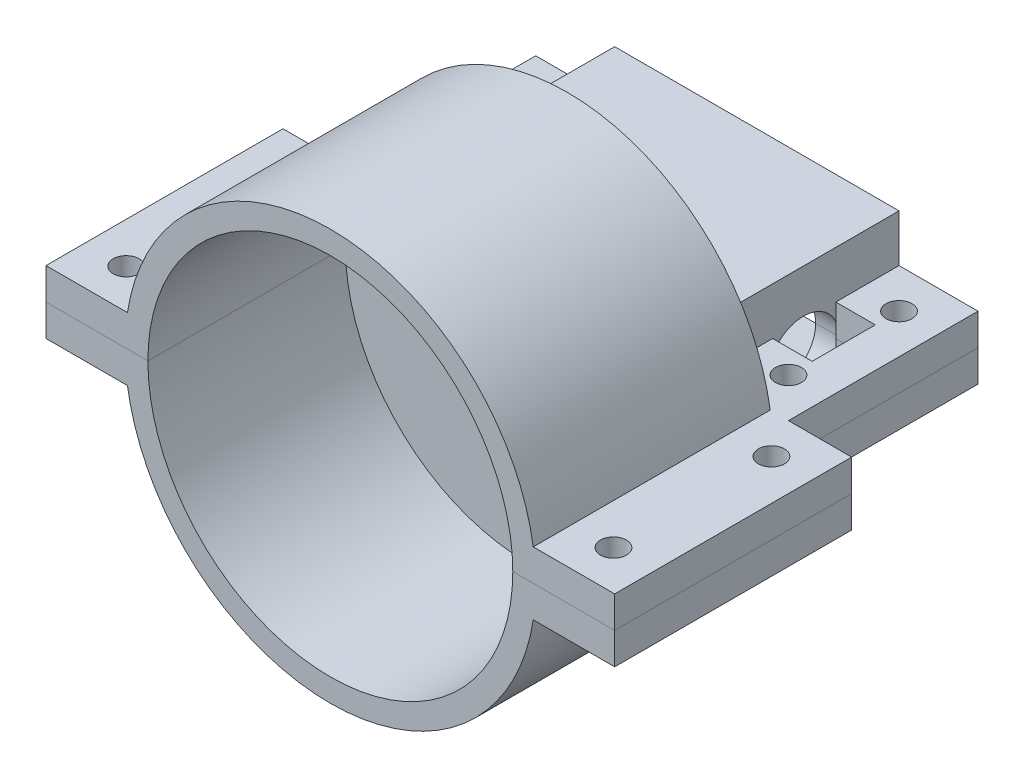
SolidWorks part; units mm, degrees
material "ABS"
ref_plane "正面" through (0, 0, 0) normal (0, 0, 1) x (1, 0, 0)
ref_plane "平面" through (0, 0, 0) normal (0, 1, 0) x (1, 0, 0)
ref_plane "右側面" through (0, 0, 0) normal (1, 0, 0) x (0, 0, -1)
sketch "ｽｹｯﾁ1" plane through (0, 0, 0) normal (0, 0, 1) x (1, 0, 0)
  circle A0 centre (0, 0) radius 26
  circle A1 centre (0, 0) radius 23.1
  dimension "D1" = 46.2
  dimension "D2" = 52
extrude "ﾎﾞｽ - 押し出し1" add sketch "ｽｹｯﾁ1" along normal blind 25
sketch "ｽｹｯﾁ2" plane through (0, 0, 0) normal (0, 0, -1) x (-1, 0, 0)
  circle A0 centre (0, 0) radius 26
extrude "ﾎﾞｽ - 押し出し2" add sketch "ｽｹｯﾁ2" along normal blind 5
sketch "ｽｹｯﾁ3" plane through (0, 0, -5) normal (0, 0, -1) x (-1, 0, 0)
  line L1 (-15.05, -7.6) -> (15.05, -7.6)
  line L2 (-15.05, -7.6) -> (-15.05, 7.6)
  line L3 (-15.05, 7.6) -> (15.05, 7.6)
  line L4 (15.05, -7.6) -> (15.05, 7.6)
  line L5 (-15.05, -7.6) -> (15.05, 7.6) construction
  line L6 (-15.05, 7.6) -> (15.05, -7.6) construction
  line L7 (-18, -10) -> (18, -10)
  line L8 (-18, -10) -> (-18, 10)
  line L9 (-18, 10) -> (18, 10)
  line L10 (18, -10) -> (18, 10)
  line L11 (-18, -10) -> (18, 10) construction
  line L12 (-18, 10) -> (18, -10) construction
  point P0 (0, 0)
  point P6 (0, 0)
  dimension "D1" = 15.2
  dimension "D2" = 30.1
  dimension "D3" = 20
  dimension "D4" = 36
extrude "ﾎﾞｽ - 押し出し3" add sketch "ｽｹｯﾁ3" along normal blind 24
sketch "ｽｹｯﾁ4" plane through (18, 0, 0) normal (1, 0, 0) x (0, 0, -1)
  line L0 (0, 0) -> (29, 0) construction
  line L1 (29, 10) -> (29, -10) construction
  circle A0 centre (16.9, 0) radius 4.5
  dimension "D2" = 9
  dimension "D1" = 12.1
extrude "ｶｯﾄ - 押し出し1" cut sketch "ｽｹｯﾁ4" against normal up to surface (36 mm away) up to face at (-18, 0, -17)
ref_plane "平面1" through (0, 0, 0) normal (0, 1, 0) x (1, 0, 0)
sketch "ｽｹｯﾁ5" plane through (0, 0, 0) normal (0, 1, 0) x (1, 0, 0)
  line L0 (18, 5) -> (28, 5)
  line L1 (28, 5) -> (28, 29)
  line L2 (28, 29) -> (18, 29)
  line L3 (18, 29) -> (18, 5)
  line L4 (25, -25) -> (36, -25)
  line L5 (36, -25) -> (36, 5)
  line L6 (36, 5) -> (25, 5)
  line L8 (25, 5) -> (25, -25)
  line L9 (0, 0) -> (0, 29) construction
  line L10 (-18, 29) -> (18, 29) construction
  line L11 (-36, 5) -> (-25, 5)
  line L12 (-36, -25) -> (-36, 5)
  line L13 (-25, -25) -> (-36, -25)
  line L14 (-25, 5) -> (-25, -25)
  line L15 (-28, 29) -> (-18, 29)
  line L16 (-28, 5) -> (-28, 29)
  line L17 (-18, 5) -> (-28, 5)
  line L18 (-18, 29) -> (-18, 5)
  line L19 (26, -25) -> (26, 5) construction
  dimension "D1" = 10
  dimension "D2" = 11
  dimension "D3" = 1
extrude "ﾎﾞｽ - 押し出し4" add sketch "ｽｹｯﾁ5" along normal blind 4 and the other way blind 4 contours L0 L8 L4 L5 L6 | L2 L3 L0 L1 | L18 L15 L16 L11 L17 | L14 L11 L12 L13
sketch "ｽｹｯﾁ6" plane through (0, 4, 0) normal (0, 1, 0) x (1, 0, 0)
  line L0 (23, 29) -> (23, 5) construction
  line L1 (28, 29) -> (18, 29) construction
  line L2 (18, 5) -> (25.6905, 5) construction
  line L3 (30.8452, -25) -> (30.8452, 5) construction
  line L4 (25.6905, -25) -> (36, -25) construction
  line L5 (28, 5) -> (36, 5) construction
  line L6 (18, 21) -> (23, 21)
  line L7 (18, 29) -> (18, 18.9616) construction
  line L8 (23, 21) -> (23, 13)
  line L9 (23, 13) -> (18, 13)
  line L10 (18, 14.8384) -> (18, 5) construction
  line L11 (18, 13) -> (18, 21)
  line L12 (0, 0) -> (0, 29) construction
  line L13 (-18, 29) -> (18, 29) construction
  line L14 (-23, 13) -> (-18, 13)
  line L15 (-23, 21) -> (-23, 13)
  line L16 (-18, 21) -> (-23, 21)
  line L17 (-18, 13) -> (-18, 21)
  circle A0 centre (23, 24) radius 1.65
  circle A1 centre (23, 10) radius 1.65
  circle A2 centre (30.8452, 0) radius 1.65
  circle A3 centre (30.8452, -20) radius 1.65
  circle A4 centre (-30.8452, -20) radius 1.65
  circle A5 centre (-30.8452, 0) radius 1.65
  circle A6 centre (-23, 10) radius 1.65
  circle A7 centre (-23, 24) radius 1.65
  dimension "D5" = 3.3
  dimension "D1" = 5
  dimension "D2" = 5
  dimension "D3" = 5
  dimension "D4" = 5
  dimension "D6" = 8
  dimension "D7" = 8
extrude "ｶｯﾄ - 押し出し2" cut sketch "ｽｹｯﾁ6" against normal up to next
split "部品分割1" trim tools "平面1" bodies to split 106 resulting bodies 107 108
